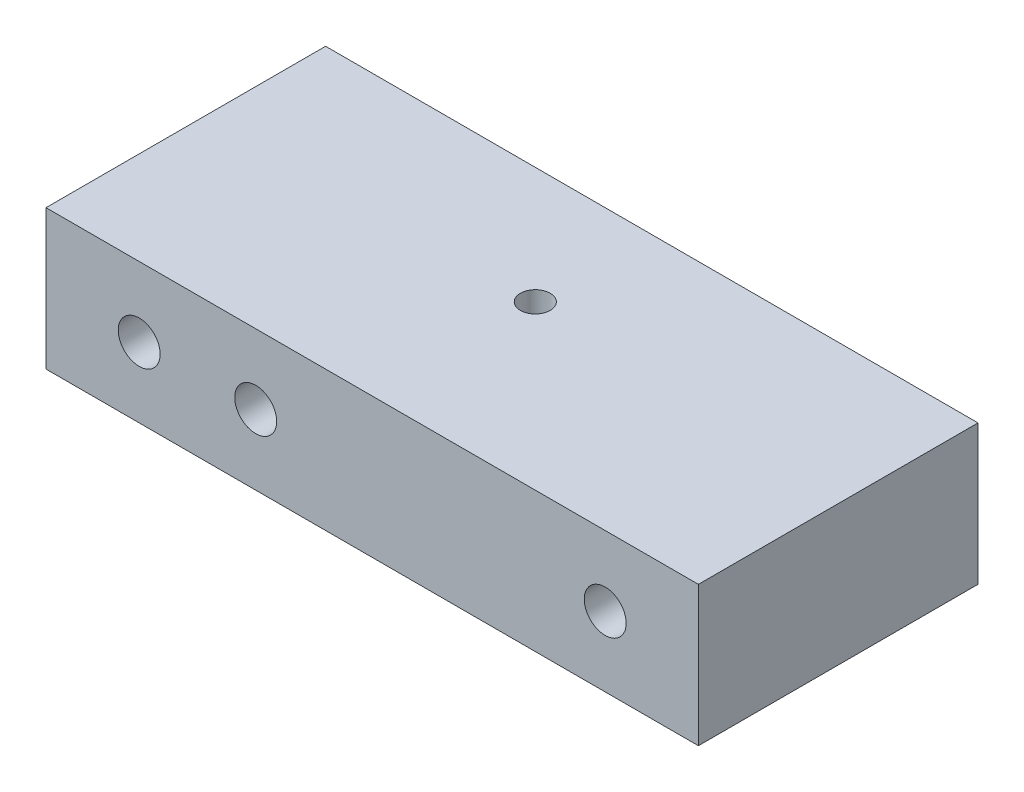
SolidWorks part; units mm, degrees
ref_plane "Front Plane" through (0, 0, 0) normal (0, 0, 1) x (1, 0, 0)
ref_plane "Top Plane" through (0, 0, 0) normal (0, 1, 0) x (1, 0, 0)
ref_plane "Right Plane" through (0, 0, 0) normal (1, 0, 0) x (0, 0, -1)
sketch "Sketch1" plane through (0, 0, 0) normal (0, 1, 0) x (1, 0, 0)
  line L1 (-70, 30) -> (70, 30)
  line L2 (-70, 30) -> (-70, -30)
  line L3 (-70, -30) -> (70, -30)
  line L4 (70, 30) -> (70, -30)
  line L5 (-70, 30) -> (70, -30) construction
  line L6 (-70, -30) -> (70, 30) construction
  point P0 (0, 0)
  dimension "D1" = 60
  dimension "D2" = 140
extrude "Boss-Extrude1" add sketch "Sketch1" along normal blind 30
sketch "Sketch2" plane through (0, 0, 30) normal (0, 0, 1) x (1, 0, 0)
  line L0 (0, 0) -> (0, 30) construction
  line L1 (-70, 0) -> (70, 0) construction
  line L2 (-70, 30) -> (70, 30) construction
  line L3 (0, 15) -> (50, 15) construction
  line L4 (0, 15) -> (-50, 15) construction
  line L5 (0, 15) -> (-25, 15)
  circle A0 centre (50, 15) radius 4.5
  circle A1 centre (-50, 15) radius 4.5
  circle A2 centre (-25, 15) radius 4.5
  dimension "D4" = 9
  dimension "D5" = 9
  dimension "D6" = 9
  dimension "D1" = 50
  dimension "D2" = 50
  dimension "D3" = 25
sketch "Sketch3" plane through (0, 30, 0) normal (0, 1, 0) x (1, 0, 0)
  line L0 (0, -30) -> (0, 5) construction
  circle A0 centre (0, 5) radius 3.2
  dimension "D2" = 6.4
  dimension "D1" = 35
extrude "Cut-Extrude1" cut sketch "Sketch2" against normal blind 60 contours A0 | A1 | A2
extrude "Cut-Extrude2" cut sketch "Sketch3" against normal blind 30 contours A0
